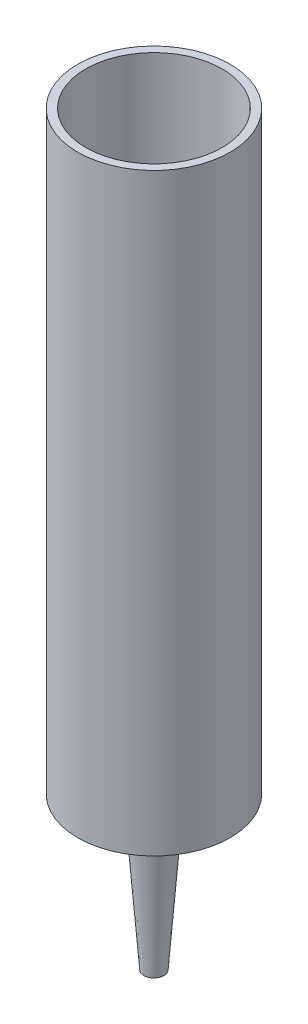
SolidWorks part; units mm, degrees
ref_plane "前视基准面" through (0, 0, 0) normal (0, 0, 1) x (1, 0, 0)
ref_plane "上视基准面" through (0, 0, 0) normal (0, 1, 0) x (1, 0, 0)
ref_plane "右视基准面" through (0, 0, 0) normal (1, 0, 0) x (0, 0, -1)
sketch "草图1" plane through (0, 0, 0) normal (0, 1, 0) x (1, 0, 0)
  circle A0 centre (0, 0) radius 19
  circle A1 centre (0, 0) radius 17
  dimension "D1" = 38
  dimension "D2" = 34
extrude "凸台-拉伸1" add sketch "草图1" along normal blind 148
sketch "草图6" plane through (0, 0, 0) normal (0, 0, 1) x (1, 0, 0)
  line L0 (-19, 0) -> (-17, 0)
  line L1 (-19, 0) -> (19, 0) construction
  line L2 (-19, 0) -> (-5, -5)
  line L3 (0, 0) -> (0, -20.3406) construction
  line L4 (0, 0) -> (33.0491, 0) construction
  line L5 (-2.5, -38) -> (-1.5, -38)
  line L6 (-5, -5) -> (-2.5, -38)
  line L7 (-17, 0) -> (-4.0278, -4.6329)
  line L8 (-4.0278, -4.6329) -> (-1.5, -38)
  dimension "D1" = 2
  dimension "D2" = 1
  dimension "D3" = 4.332
  dimension "D4" = 5
  dimension "D5" = 5
  dimension "D6" = 38
revolve "旋转1" add sketch "草图6" angle 360 about L3
